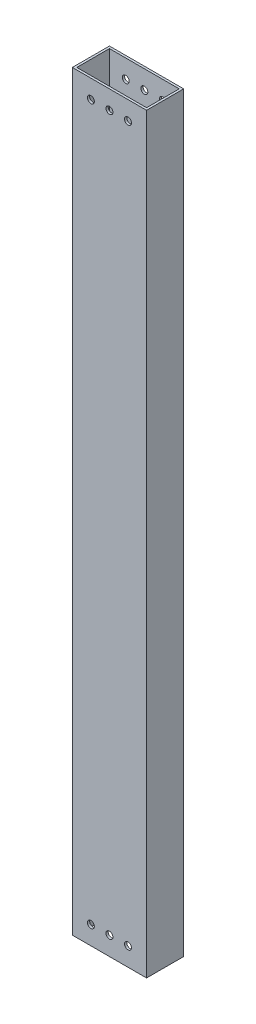
SolidWorks part; units mm, degrees
ref_plane "Front Plane" through (0, 0, 0) normal (0, 0, 1) x (1, 0, 0)
ref_plane "Top Plane" through (0, 0, 0) normal (0, 1, 0) x (1, 0, 0)
ref_plane "Right Plane" through (0, 0, 0) normal (1, 0, 0) x (0, 0, -1)
sketch "Sketch1" plane through (0, 0, 0) normal (0, 1, 0) x (1, 0, 0)
  line L1 (0, 0) -> (-50.8, 0)
  line L2 (0, 0) -> (0, -25.4)
  line L3 (0, -25.4) -> (-50.8, -25.4)
  line L4 (-50.8, 0) -> (-50.8, -25.4)
  dimension "D1" = 50.8
  dimension "D2" = 25.4
extrude "Extrude-Thin1" add sketch "Sketch1" along normal blind 514.35 thin thin type one direction reverse wall 1.524
sketch "Sketch2" plane through (0, 0, 25.4) normal (0, 0, 1) x (1, 0, 0)
  line L0 (0, 514.35) -> (0, 0) construction
  line L1 (-50.8, 0) -> (0, 0) construction
  line L2 (-191.8541, 257.175) -> (213.5558, 257.175)
  line L3 (-50.8, 514.35) -> (0, 514.35) construction
  circle A0 centre (-38.1, 12.7) radius 2.3812
  circle A1 centre (-25.4, 12.7) radius 2.3812
  circle A2 centre (-12.7, 12.7) radius 2.3813
  circle A3 centre (-12.7, 501.65) radius 2.3813
  circle A4 centre (-25.4, 501.65) radius 2.3813
  circle A5 centre (-38.1, 501.65) radius 2.3813
  dimension "D1" = 4.7625
  dimension "D2" = 4.7625
  dimension "D3" = 4.7625
  dimension "D4" = 12.7
  dimension "D5" = 12.7
  dimension "D6" = 12.7
  dimension "D7" = 12.7
  dimension "D8" = 12.7
  dimension "D9" = 257.175
extrude "Cut-Extrude1" cut sketch "Sketch2" against normal through all both and the other way through all contours A0 | A1 | A2 | A5 | A4 | A3
